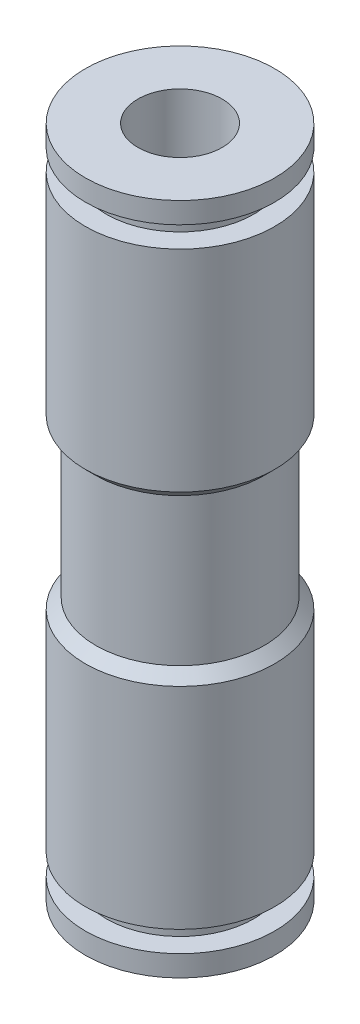
SolidWorks part; units mm, degrees
ref_plane "Спереди" through (0, 0, 0) normal (0, 0, 1) x (1, 0, 0)
ref_plane "Сверху" through (0, 0, 0) normal (0, 1, 0) x (1, 0, 0)
ref_plane "Справа" through (0, 0, 0) normal (1, 0, 0) x (0, 0, -1)
sketch "Эскиз1" plane through (0, 0, 0) normal (0, 0, 1) x (1, 0, 0)
  line L0 (0, 64.6276) -> (0, -47.9072) construction
  line L1 (4.5, 16) -> (2, 16)
  line L2 (4.5, 16) -> (4.5, 15)
  line L3 (4.5, 15) -> (3.5, 15)
  line L4 (3.5, 15) -> (3.5, 14)
  line L5 (3.5, 14) -> (4.5, 14)
  line L6 (4.5, 14) -> (4.5, 4)
  line L7 (4.5, 4) -> (4, 3.5)
  line L8 (4, 3.5) -> (4, 0)
  line L9 (2, 16) -> (2, 0)
  line L11 (2, 0) -> (4, 0)
  dimension "D1" = 2
  dimension "D2" = 2.5
  dimension "D3" = 2
  dimension "D4" = 135
  dimension "D5" = 16
  dimension "D6" = 1
  dimension "D7" = 1
  dimension "D8" = 1
  dimension "D9" = 10
revolve "Повернуть1" add sketch "Эскиз1" angle 360 about L0
mirror "Зеркальное отражение1" of "Повернуть1"
